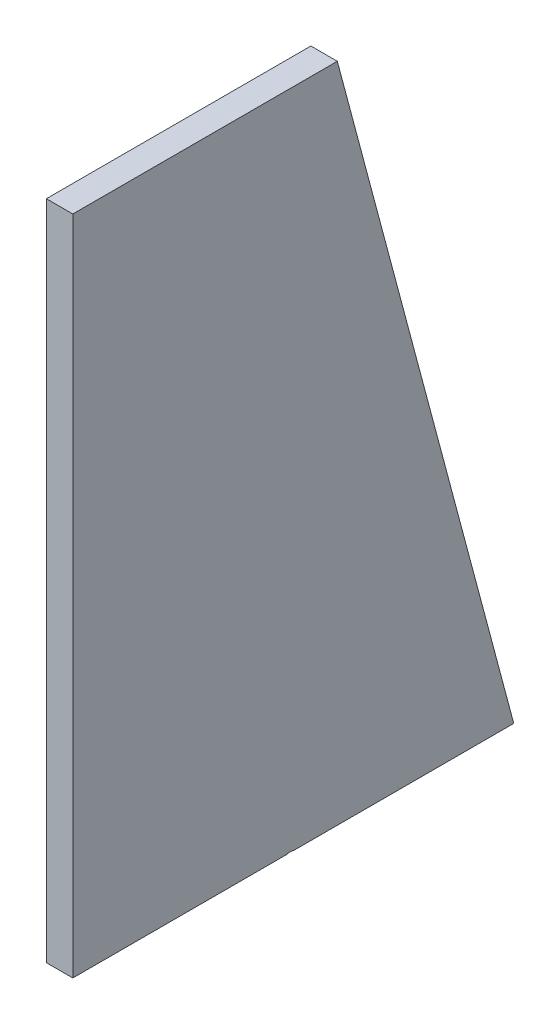
SolidWorks part; units mm, degrees
ref_plane "Спереди" through (0, 0, 0) normal (0, 0, 1) x (1, 0, 0)
ref_plane "Сверху" through (0, 0, 0) normal (0, 1, 0) x (1, 0, 0)
ref_plane "Справа" through (0, 0, 0) normal (1, 0, 0) x (0, 0, -1)
sketch "Эскиз1" plane through (0, 0, 0) normal (1, 0, 0) x (0, 0, -1)
  line L0 (0, 0) -> (100, 0)
  line L1 (0, 0) -> (0, 150)
  line L2 (0, 150) -> (60, 150)
  line L3 (60, 150) -> (100, 0)
extrude "Бобышка-Вытянуть1" add sketch "Эскиз1" along normal blind 6
sketch "Sketch1" plane through (0, 0, 0) normal (0, -1, 0) x (1, 0, 0)
  line L0 (3, 0) -> (3, -100) construction
  line L1 (6, 0) -> (0, 0) construction
  line L2 (6, -100) -> (0, -100) construction
  line L3 (0.0053, -49.8214) -> (1.2531, -28.8958)
  line L4 (4.7469, -28.8958) -> (5.9947, -49.8214)
  line L5 (0, -48.5913) -> (6, -48.5913)
  line L6 (6, 0) -> (0, 0)
  line L7 (6, 0) -> (6, -100)
  line L8 (6, -100) -> (0, -100)
  line L9 (0, 0) -> (0, -100)
  circle A0 centre (3, -50) radius 3
  circle A1 centre (3, -29) radius 1.75
  line M2 (0, 0) -> (0, -100)
  line M3 (0, -100) -> (6, -100)
  line M4 (6, -100) -> (6, 0)
  line M5 (6, 0) -> (0, 0)
  dimension "D2" = 3.5
  dimension "D3" = 6
  dimension "D1" = 21
extrude "Boss-Extrude4" add sketch "Sketch1" along normal blind 0.1 contours L0 L6 L5 L3 A1 M2 | L0 A1 L4 L5 M5 M4 | A0 L0 L8 M4 | L0 A0 L9 M3
